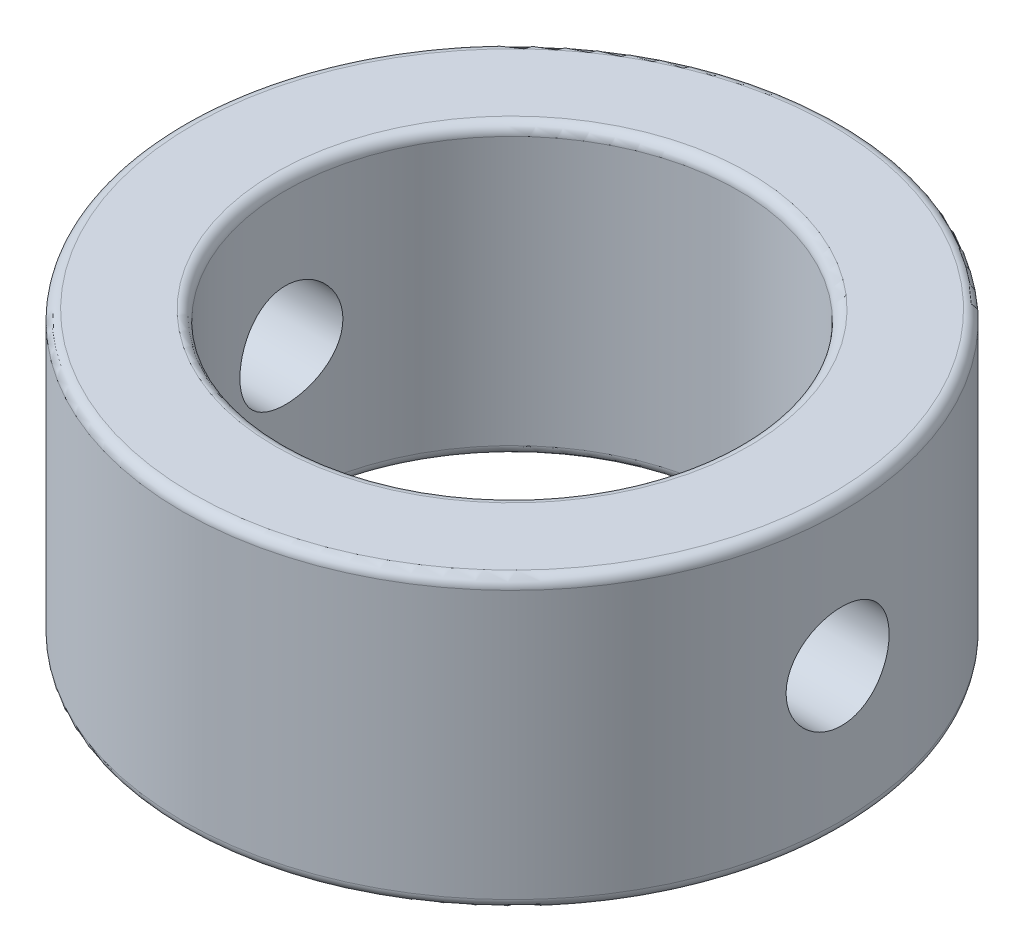
SolidWorks part; units mm, degrees
ref_plane "Front Plane" through (0, 0, 0) normal (0, 0, 1) x (1, 0, 0)
ref_plane "Top Plane" through (0, 0, 0) normal (0, 1, 0) x (1, 0, 0)
ref_plane "Right Plane" through (0, 0, 0) normal (1, 0, 0) x (0, 0, -1)
sketch "Sketch1" plane through (0, 0, 0) normal (0, 1, 0) x (1, 0, 0)
  circle A0 centre (0, 0) radius 11
  circle A1 centre (0, 0) radius 16
  dimension "D1" = 22
  dimension "D2" = 32
extrude "Boss-Extrude1" add sketch "Sketch1" along normal mid plane 14
sketch "Sketch2" plane through (0, 0, 0) normal (1, 0, 0) x (0, 0, -1)
  circle A0 centre (0, 0) radius 2.5
  dimension "D1" = 5
extrude "Cut-Extrude1" cut sketch "Sketch2" against normal through all both and the other way through all
fillet "Fillet1" radius 0.5 4 edges at (0, -7, 11) (0, -7, 16) (0, 7, 11) (0, 7, 16)
